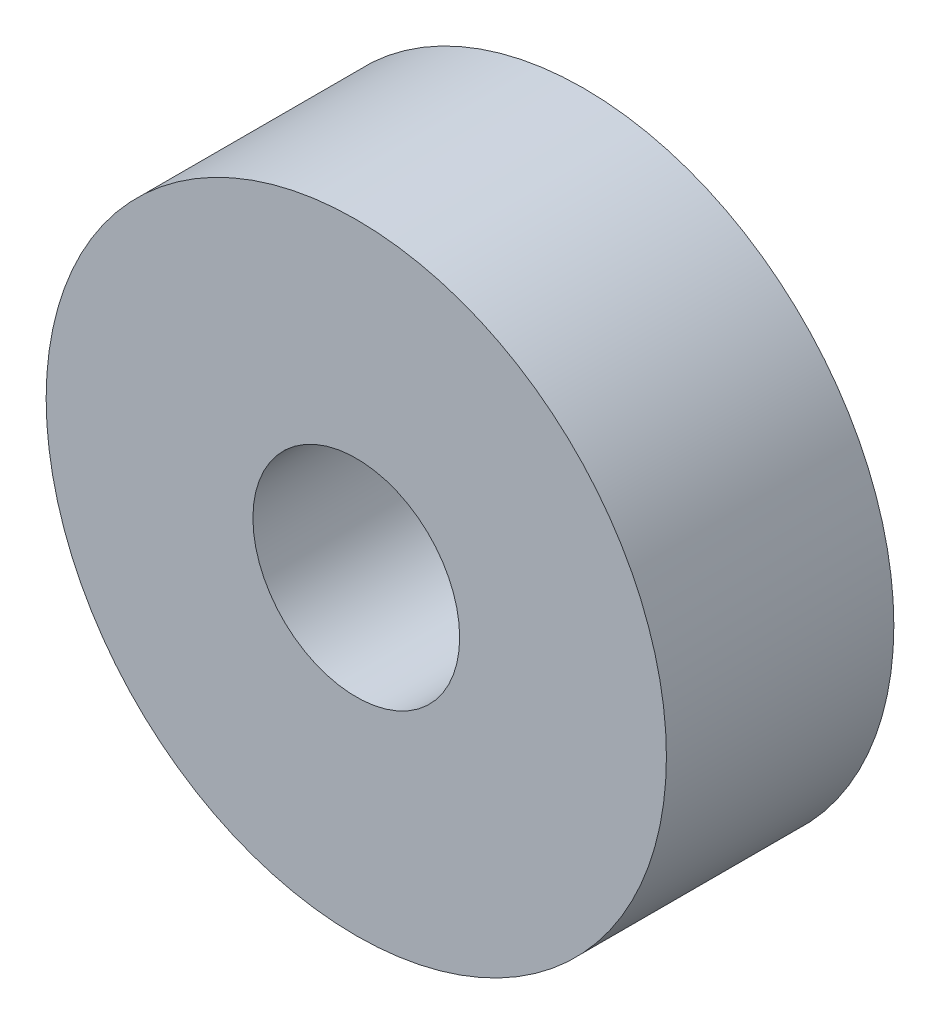
SolidWorks part; units mm, degrees
ref_plane "Front Plane" through (0, 0, 0) normal (0, 0, 1) x (1, 0, 0)
ref_plane "Top Plane" through (0, 0, 0) normal (0, 1, 0) x (1, 0, 0)
ref_plane "Right Plane" through (0, 0, 0) normal (1, 0, 0) x (0, 0, -1)
sketch "Sketch1" plane through (0, 0, 0) normal (0, 0, 1) x (1, 0, 0)
  circle A0 centre (0, 0) radius 1
  circle A1 centre (0, 0) radius 3
  dimension "D1" = 2
  dimension "D2" = 6
extrude "Boss-Extrude1" add sketch "Sketch1" along normal blind 2.2
